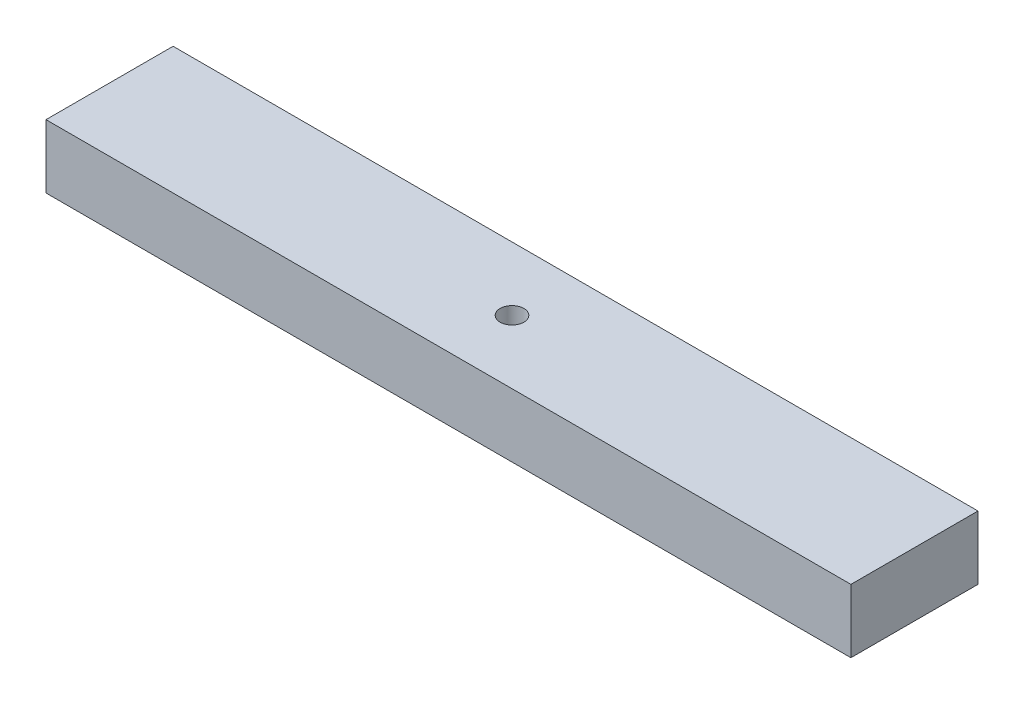
SolidWorks part; units mm, degrees
material "Sapin"
ref_plane "Plan de face" through (0, 0, 0) normal (0, 0, 1) x (1, 0, 0)
ref_plane "Plan de dessus" through (0, 0, 0) normal (0, 1, 0) x (1, 0, 0)
ref_plane "Plan de droite" through (0, 0, 0) normal (1, 0, 0) x (0, 0, -1)
sketch "Esquisse1" plane through (0, 0, 0) normal (0, 1, 0) x (1, 0, 0)
  line L1 (-152, -24) -> (152, -24)
  line L2 (-152, -24) -> (-152, 24)
  line L3 (-152, 24) -> (152, 24)
  line L4 (152, -24) -> (152, 24)
  line L5 (-152, -24) -> (152, 24) construction
  line L6 (-152, 24) -> (152, -24) construction
  point P0 (0, 0)
  dimension "D1" = 304
  dimension "D2" = 48
extrude "Boss.-Extru.1" add sketch "Esquisse1" along normal blind 24
sketch "Esquisse2" plane through (0, 24, 0) normal (0, 1, 0) x (1, 0, 0)
  circle A0 centre (0, 0) radius 4.5
  dimension "D1" = 9
extrude "Enlèv. mat.-Extru.1" cut sketch "Esquisse2" against normal through all
sketch "Esquisse3" plane through (0, 0, 0) normal (0, -1, 0) x (1, 0, 0)
  circle A0 centre (0, 0) radius 7
  dimension "D1" = 14
extrude "Enlèv. mat.-Extru.2" cut sketch "Esquisse3" against normal blind 12
